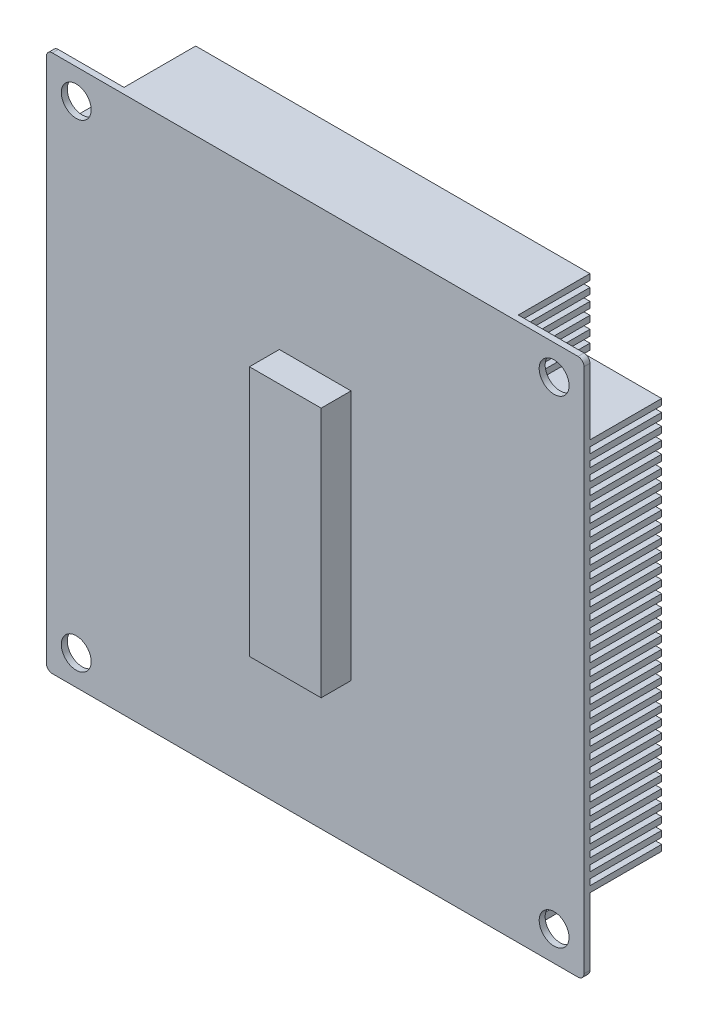
SolidWorks part; units mm, degrees
material "铜"
ref_plane "前视基准面" through (0, 0, 0) normal (0, 0, 1) x (1, 0, 0)
ref_plane "上视基准面" through (0, 0, 0) normal (0, 1, 0) x (1, 0, 0)
ref_plane "右视基准面" through (0, 0, 0) normal (1, 0, 0) x (0, 0, -1)
sketch "草图1" plane through (0, 0, 0) normal (0, 0, 1) x (1, 0, 0)
  line L14 (-95.9917, -50.2959) -> (-5.9917, -50.2959)
  line L15 (-95.9917, -50.2959) -> (-95.9917, 39.7041)
  line L16 (-95.9917, 39.7041) -> (-5.9917, 39.7041)
  line L17 (-5.9917, -50.2959) -> (-5.9917, 39.7041)
extrude "凸台-拉伸1" add sketch "草图1" along normal blind 13
sketch "草图2" plane through (0, 0, 13) normal (0, 0, 1) x (1, 0, 0)
  line L0 (-5.9917, 39.7041) -> (-95.9917, 39.7041) construction
  line L1 (-56.9917, 15.7041) -> (-44.9917, 15.7041)
  line L2 (-56.9917, 15.7041) -> (-56.9917, -26.2959)
  line L3 (-56.9917, -26.2959) -> (-44.9917, -26.2959)
  line L4 (-44.9917, 15.7041) -> (-44.9917, -26.2959)
  line L7 (-95.9917, 39.7041) -> (-95.9917, -50.2959) construction
  dimension "D1" = 24
  dimension "D2" = 39
  dimension "D3" = 42
  dimension "D4" = 12
extrude "凸台-拉伸2" add sketch "草图2" along normal blind 5
sketch "草图5" plane through (-95.9917, 0, 0) normal (-1, 0, 0) x (0, 0, 1)
  line L0 (13, 39.7041) -> (0, 39.7041) construction
  line L1 (0, 38.7041) -> (12, 38.7041)
  line L2 (0, 38.7041) -> (0, 37.7041)
  line L3 (0, 37.7041) -> (12, 37.7041)
  line L4 (12, 38.7041) -> (12, 37.7041)
  line L5 (13, 39.7041) -> (13, -50.2959) construction
  line L6 (0, 39.7041) -> (0, -50.2959) construction
  line L7 (0, 36.6841) -> (0, 35.6841)
  line L8 (0, 36.6841) -> (12, 36.6841)
  line L9 (12, 36.6841) -> (12, 35.6841)
  line L10 (0, 35.6841) -> (12, 35.6841)
  line L11 (0, 34.6641) -> (0, 33.6641)
  line L12 (0, 34.6641) -> (12, 34.6641)
  line L13 (12, 34.6641) -> (12, 33.6641)
  line L14 (0, 33.6641) -> (12, 33.6641)
  line L15 (0, 32.6441) -> (0, 31.6441)
  line L16 (0, 32.6441) -> (12, 32.6441)
  line L17 (12, 32.6441) -> (12, 31.6441)
  line L18 (0, 31.6441) -> (12, 31.6441)
  line L19 (0, 30.6241) -> (0, 29.6241)
  line L20 (0, 30.6241) -> (12, 30.6241)
  line L21 (12, 30.6241) -> (12, 29.6241)
  line L22 (0, 29.6241) -> (12, 29.6241)
  line L23 (0, 28.6041) -> (0, 27.6041)
  line L24 (0, 28.6041) -> (12, 28.6041)
  line L25 (12, 28.6041) -> (12, 27.6041)
  line L26 (0, 27.6041) -> (12, 27.6041)
  line L27 (0, 26.5841) -> (0, 25.5841)
  line L28 (0, 26.5841) -> (12, 26.5841)
  line L29 (12, 26.5841) -> (12, 25.5841)
  line L30 (0, 25.5841) -> (12, 25.5841)
  line L31 (0, 24.5641) -> (0, 23.5641)
  line L32 (0, 24.5641) -> (12, 24.5641)
  line L33 (12, 24.5641) -> (12, 23.5641)
  line L34 (0, 23.5641) -> (12, 23.5641)
  line L35 (0, 22.5441) -> (0, 21.5441)
  line L36 (0, 22.5441) -> (12, 22.5441)
  line L37 (12, 22.5441) -> (12, 21.5441)
  line L38 (0, 21.5441) -> (12, 21.5441)
  line L39 (0, 20.5241) -> (0, 19.5241)
  line L40 (0, 20.5241) -> (12, 20.5241)
  line L41 (12, 20.5241) -> (12, 19.5241)
  line L42 (0, 19.5241) -> (12, 19.5241)
  line L43 (0, 18.5041) -> (0, 17.5041)
  line L44 (0, 18.5041) -> (12, 18.5041)
  line L45 (12, 18.5041) -> (12, 17.5041)
  line L46 (0, 17.5041) -> (12, 17.5041)
  line L47 (0, 16.4841) -> (0, 15.4841)
  line L48 (0, 16.4841) -> (12, 16.4841)
  line L49 (12, 16.4841) -> (12, 15.4841)
  line L50 (0, 15.4841) -> (12, 15.4841)
  line L51 (0, 14.4641) -> (0, 13.4641)
  line L52 (0, 14.4641) -> (12, 14.4641)
  line L53 (12, 14.4641) -> (12, 13.4641)
  line L54 (0, 13.4641) -> (12, 13.4641)
  line L55 (0, 12.4441) -> (0, 11.4441)
  line L56 (0, 12.4441) -> (12, 12.4441)
  line L57 (12, 12.4441) -> (12, 11.4441)
  line L58 (0, 11.4441) -> (12, 11.4441)
  line L59 (0, 10.4241) -> (0, 9.4241)
  line L60 (0, 10.4241) -> (12, 10.4241)
  line L61 (12, 10.4241) -> (12, 9.4241)
  line L62 (0, 9.4241) -> (12, 9.4241)
  line L63 (0, 8.4041) -> (0, 7.4041)
  line L64 (0, 8.4041) -> (12, 8.4041)
  line L65 (12, 8.4041) -> (12, 7.4041)
  line L66 (0, 7.4041) -> (12, 7.4041)
  line L67 (0, 6.3841) -> (0, 5.3841)
  line L68 (0, 6.3841) -> (12, 6.3841)
  line L69 (12, 6.3841) -> (12, 5.3841)
  line L70 (0, 5.3841) -> (12, 5.3841)
  line L71 (0, 4.3641) -> (0, 3.3641)
  line L72 (0, 4.3641) -> (12, 4.3641)
  line L73 (12, 4.3641) -> (12, 3.3641)
  line L74 (0, 3.3641) -> (12, 3.3641)
  line L75 (0, 2.3441) -> (0, 1.3441)
  line L76 (0, 2.3441) -> (12, 2.3441)
  line L77 (12, 2.3441) -> (12, 1.3441)
  line L78 (0, 1.3441) -> (12, 1.3441)
  line L79 (0, 0.3241) -> (0, -0.6759)
  line L80 (0, 0.3241) -> (12, 0.3241)
  line L81 (12, 0.3241) -> (12, -0.6759)
  line L82 (0, -0.6759) -> (12, -0.6759)
  line L83 (0, -1.6959) -> (0, -2.6959)
  line L84 (0, -1.6959) -> (12, -1.6959)
  line L85 (12, -1.6959) -> (12, -2.6959)
  line L86 (0, -2.6959) -> (12, -2.6959)
  line L87 (0, -3.7159) -> (0, -4.7159)
  line L88 (0, -3.7159) -> (12, -3.7159)
  line L89 (12, -3.7159) -> (12, -4.7159)
  line L90 (0, -4.7159) -> (12, -4.7159)
  line L91 (0, -5.7359) -> (0, -6.7359)
  line L92 (0, -5.7359) -> (12, -5.7359)
  line L93 (12, -5.7359) -> (12, -6.7359)
  line L94 (0, -6.7359) -> (12, -6.7359)
  line L95 (0, -7.7559) -> (0, -8.7559)
  line L96 (0, -7.7559) -> (12, -7.7559)
  line L97 (12, -7.7559) -> (12, -8.7559)
  line L98 (0, -8.7559) -> (12, -8.7559)
  line L99 (0, -9.7759) -> (0, -10.7759)
  line L100 (0, -9.7759) -> (12, -9.7759)
  line L101 (12, -9.7759) -> (12, -10.7759)
  line L102 (0, -10.7759) -> (12, -10.7759)
  line L103 (0, -11.7959) -> (0, -12.7959)
  line L104 (0, -11.7959) -> (12, -11.7959)
  line L105 (12, -11.7959) -> (12, -12.7959)
  line L106 (0, -12.7959) -> (12, -12.7959)
  line L107 (0, -13.8159) -> (0, -14.8159)
  line L108 (0, -13.8159) -> (12, -13.8159)
  line L109 (12, -13.8159) -> (12, -14.8159)
  line L110 (0, -14.8159) -> (12, -14.8159)
  line L111 (0, -15.8359) -> (0, -16.8359)
  line L112 (0, -15.8359) -> (12, -15.8359)
  line L113 (12, -15.8359) -> (12, -16.8359)
  line L114 (0, -16.8359) -> (12, -16.8359)
  line L115 (0, -17.8559) -> (0, -18.8559)
  line L116 (0, -17.8559) -> (12, -17.8559)
  line L117 (12, -17.8559) -> (12, -18.8559)
  line L118 (0, -18.8559) -> (12, -18.8559)
  line L119 (0, -19.8759) -> (0, -20.8759)
  line L120 (0, -19.8759) -> (12, -19.8759)
  line L121 (12, -19.8759) -> (12, -20.8759)
  line L122 (0, -20.8759) -> (12, -20.8759)
  line L123 (0, -21.8959) -> (0, -22.8959)
  line L124 (0, -21.8959) -> (12, -21.8959)
  line L125 (12, -21.8959) -> (12, -22.8959)
  line L126 (0, -22.8959) -> (12, -22.8959)
  line L127 (0, -23.9159) -> (0, -24.9159)
  line L128 (0, -23.9159) -> (12, -23.9159)
  line L129 (12, -23.9159) -> (12, -24.9159)
  line L130 (0, -24.9159) -> (12, -24.9159)
  line L131 (0, -25.9359) -> (0, -26.9359)
  line L132 (0, -25.9359) -> (12, -25.9359)
  line L133 (12, -25.9359) -> (12, -26.9359)
  line L134 (0, -26.9359) -> (12, -26.9359)
  line L135 (0, -27.9559) -> (0, -28.9559)
  line L136 (0, -27.9559) -> (12, -27.9559)
  line L137 (12, -27.9559) -> (12, -28.9559)
  line L138 (0, -28.9559) -> (12, -28.9559)
  line L139 (0, -29.9759) -> (0, -30.9759)
  line L140 (0, -29.9759) -> (12, -29.9759)
  line L141 (12, -29.9759) -> (12, -30.9759)
  line L142 (0, -30.9759) -> (12, -30.9759)
  line L143 (0, -31.9959) -> (0, -32.9959)
  line L144 (0, -31.9959) -> (12, -31.9959)
  line L145 (12, -31.9959) -> (12, -32.9959)
  line L146 (0, -32.9959) -> (12, -32.9959)
  line L147 (0, -34.0159) -> (0, -35.0159)
  line L148 (0, -34.0159) -> (12, -34.0159)
  line L149 (12, -34.0159) -> (12, -35.0159)
  line L150 (0, -35.0159) -> (12, -35.0159)
  line L151 (0, -36.0359) -> (0, -37.0359)
  line L152 (0, -36.0359) -> (12, -36.0359)
  line L153 (12, -36.0359) -> (12, -37.0359)
  line L154 (0, -37.0359) -> (12, -37.0359)
  line L155 (0, -38.0559) -> (0, -39.0559)
  line L156 (0, -38.0559) -> (12, -38.0559)
  line L157 (12, -38.0559) -> (12, -39.0559)
  line L158 (0, -39.0559) -> (12, -39.0559)
  line L159 (0, -40.0759) -> (0, -41.0759)
  line L160 (0, -40.0759) -> (12, -40.0759)
  line L161 (12, -40.0759) -> (12, -41.0759)
  line L162 (0, -41.0759) -> (12, -41.0759)
  line L163 (0, -42.0959) -> (0, -43.0959)
  line L164 (0, -42.0959) -> (12, -42.0959)
  line L165 (12, -42.0959) -> (12, -43.0959)
  line L166 (0, -43.0959) -> (12, -43.0959)
  line L167 (0, -44.1159) -> (0, -45.1159)
  line L168 (0, -44.1159) -> (12, -44.1159)
  line L169 (12, -44.1159) -> (12, -45.1159)
  line L170 (0, -45.1159) -> (12, -45.1159)
  line L171 (0, -46.1359) -> (0, -47.1359)
  line L172 (0, -46.1359) -> (12, -46.1359)
  line L173 (12, -46.1359) -> (12, -47.1359)
  line L174 (0, -47.1359) -> (12, -47.1359)
  line L175 (0, -48.1559) -> (0, -49.1559)
  line L176 (0, -48.1559) -> (12, -48.1559)
  line L177 (12, -48.1559) -> (12, -49.1559)
  line L178 (0, -49.1559) -> (12, -49.1559)
  point P4 (6, 38.7041)
  dimension "D1" = 1
  dimension "D2" = 1
  dimension "D3" = 1
  dimension "D4" = 0
  dimension "D5" = 44
extrude "切除-拉伸5" cut sketch "草图5" against normal blind 90
sketch "草图6" plane through (0, 0, 0) normal (0, 0, -1) x (-1, 0, 0)
  line L12 (5.9917, -50.2959) -> (17.9917, -50.2959)
  line L13 (5.9917, -50.2959) -> (5.9917, -38.2959)
  line L14 (5.9917, -38.2959) -> (17.9917, -38.2959)
  line L15 (17.9917, -50.2959) -> (17.9917, -38.2959)
  line L16 (95.9917, -50.2959) -> (83.9917, -50.2959)
  line L17 (95.9917, -50.2959) -> (95.9917, -38.2959)
  line L18 (95.9917, -38.2959) -> (83.9917, -38.2959)
  line L19 (83.9917, -50.2959) -> (83.9917, -38.2959)
  line L20 (95.9917, 39.7041) -> (83.9917, 39.7041)
  line L21 (95.9917, 39.7041) -> (95.9917, 27.7041)
  line L22 (95.9917, 27.7041) -> (83.9917, 27.7041)
  line L23 (83.9917, 39.7041) -> (83.9917, 27.7041)
  line L24 (5.9917, 39.7041) -> (17.9917, 39.7041)
  line L25 (5.9917, 39.7041) -> (5.9917, 27.7041)
  line L26 (5.9917, 27.7041) -> (17.9917, 27.7041)
  line L27 (17.9917, 39.7041) -> (17.9917, 27.7041)
extrude "切除-拉伸6" cut sketch "草图6" against normal blind 12
sketch "草图7" plane through (0, 0, 12) normal (0, 0, -1) x (-1, 0, 0)
  line L0 (5.9917, 27.6041) -> (5.9917, 39.7041) construction
  line L1 (17.9917, 39.7041) -> (5.9917, 39.7041) construction
  line L2 (5.9917, -50.2959) -> (17.9917, -50.2959) construction
  line L4 (95.9917, 27.6041) -> (95.9917, 39.7041) construction
  circle A0 centre (10.9917, 34.7041) radius 2.5
  circle A1 centre (10.9917, -45.2959) radius 2.5
  circle A2 centre (90.9917, 34.7041) radius 2.5
  circle A3 centre (90.9917, -45.2959) radius 2.5
  dimension "D1" = 5
  dimension "D3" = 5
  dimension "D4" = 5
  dimension "D2" = 5
extrude "切除-拉伸7" cut sketch "草图7" against normal through all
fillet "圆角1" radius 1 4 edges at (-5.9917, 39.7041, 12.5) (-95.9917, 39.7041, 12.5) (-95.9917, -50.2959, 12.5) (-5.9917, -50.2959, 12.5)
